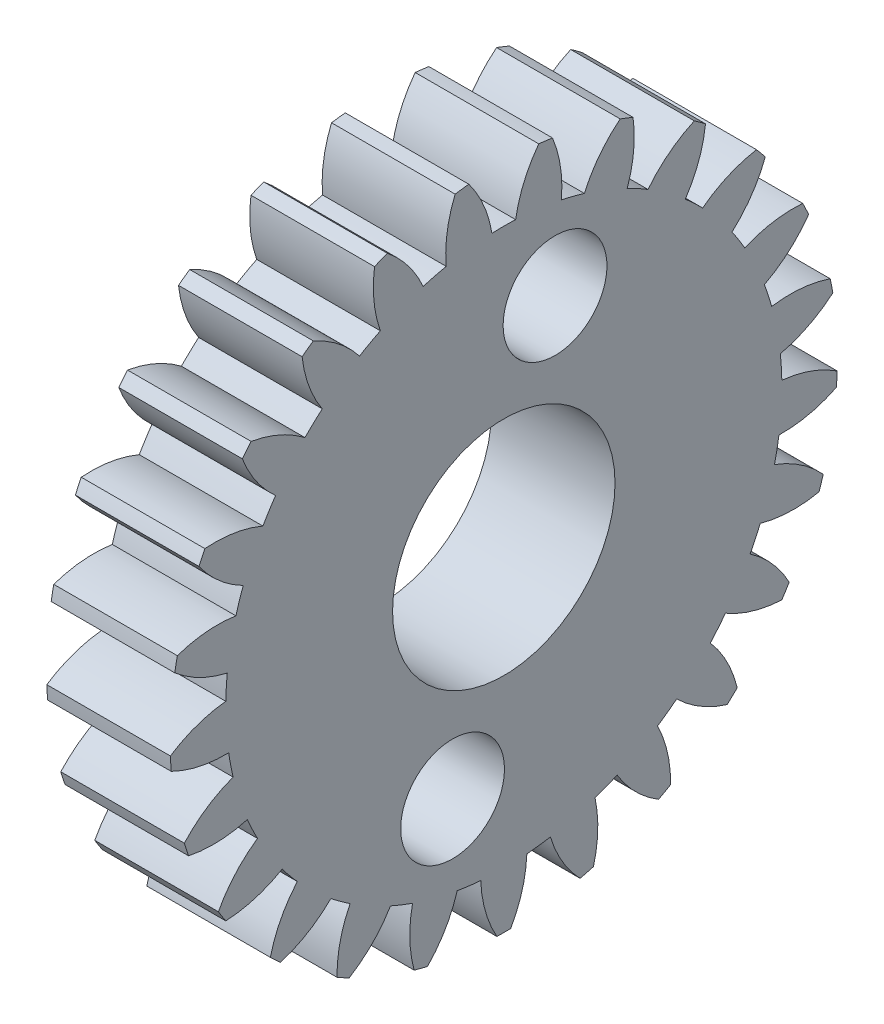
SolidWorks part; units mm, degrees
ref_plane "Plane1" through (0, 0, 0) normal (0, 0, 1) x (1, 0, 0)
ref_plane "Plane2" through (0, 0, 0) normal (0, 1, 0) x (1, 0, 0)
ref_plane "Plane3" through (0, 0, 0) normal (1, 0, 0) x (0, 0, -1)
sketch "HoldingSke" plane through (0, 0, 0) normal (0, 1, 0) x (1, 0, 0)
  line L0 (0, 0) -> (0.9063, -0.4226)
  line L1 (-15, 0) -> (100, 0) construction
  line L2 (0, 0) -> (-2.1039, 2.3779)
  line L3 (0, 0) -> (-11.863, 4.5341)
  line L4 (0, 0) -> (7.8269, 3.6497)
  line L5 (0, 0) -> (-46.8476, -17.4728)
  line L6 (0, 0) -> (-4.1448, -2.7965)
  line L7 (-2.1039, 2.3779) -> (8.6586, 51.2059)
  line L8 (-76.2, 54.61) -> (-74.8, 54.61)
  line L9 (-71.009, 38.7566) -> (-53.1078, 45.2721)
  line L10 (-76.2, 71.12) -> (104.1128, 71.12)
  line L11 (0, 0) -> (-5, 0)
  line L12 (-76.2, 101.6) -> (-76.162, 101.6)
  line L13 (24.9733, 27.94) -> (52.9518, 28.4284)
  line L14 (24.9733, 27.94) -> (24.9743, 27.94)
  line L15 (24.9733, 27.94) -> (100.4006, 29.5858)
  line L16 (-63.627, -1) -> (-12.827, -1)
  circle A0 centre (0, 0) radius 4.5
  circle A1 centre (0, 0) radius 11.249
  circle A2 centre (0, 0) radius 37.5
  circle A3 centre (0, 0) radius 4.5
  dimension "MHD" = 22.498
  dimension "Hub_dia" = 75
  dimension "Bore" = 9
  dimension "MBD" = 9
  dimension "Num_teeth" = 25
  dimension "Pitch" = 1
  dimension "Overall_len" = 50
  dimension "Show_teeth" = 25
  dimension "Thickness" = 5
  dimension "OAL" = 50.0001
  dimension "T_dim" = 1.4
  dimension "Ap" = 20
  dimension "H" = 19.05
  dimension "Pitch_radius" = 180.3128
  dimension "Width" = 5
  dimension "Backlash" = 0.038
  dimension "Addendum_fac" = 1
  dimension "Dedendum_fac" = 1.25
  dimension "Clearance_fac" = 0.25
  dimension "Dedendum_add" = 0.001
  dimension "Module" = 1
sketch "BasProSke" plane through (0, 0, 0) normal (0, 1, 0) x (1, 0, 0)
  line L0 (-10, 0) -> (60, 0) construction
  line L1 (0, 0) -> (0, 13.5)
  line L2 (0, 0) -> (5, 0)
  line L3 (5, 0) -> (5, 13.5)
  line L4 (5, 13.5) -> (0, 13.5)
  dimension "Thickness" = 5
  dimension "Diameter" = 27
revolve "Base-Revolve" add sketch "BasProSke" angle 360 about L0
sketch "TooCutSke" plane through (0, 0, 0) normal (1, 0, 0) x (0, 0, -1)
  line L1 (0, 0) -> (0, 107) construction
  line L2 (0, 0) -> (-0.8514, 12.471) construction
  line L3 (0, 0) -> (-3.1282, 24.7619) construction
  line L4 (-0.8514, 12.471) -> (-1.5641, 12.3809) construction
  arc A0 (0.4801, 11.2388) -> (-0.4801, 11.2388) centre (0, 0) ccw
  arc A1 (1.4322, 13.4494) -> (-1.4322, 13.4494) centre (0, 0) ccw
  circle A2 centre (0, 0) radius 12.5 construction
  circle A3 centre (0, 0) radius 11.7462 construction
  arc A4 (-0.4801, 11.2388) -> (-1.4322, 13.4494) centre (-5.4133, 10.4244) ccw
  arc A5 (1.4322, 13.4494) -> (0.4801, 11.2388) centre (5.4133, 10.4244) ccw
  dimension "Root_dia" = 22.498
  dimension "Overcut_dia" = 27.0508
  dimension "Pitch_dia" = 25
  dimension "Base_dia" = 23.4923
  dimension "Flank_rad" = 5
  dimension "Half_ang" = 7.2
  dimension "Half_CT" = 0.7184
extrude "ToothCut" cut sketch "TooCutSke" along normal through all
fillet "Breaks" [suppressed] radius 0.02
fillet "RootFillets" [suppressed] radius 0.251
pattern_circular "TeethCuts" count 25 every 14.4 about axis through (-10, 0, 0) along (1, 0, 0) of "ToothCut", "RootFillets", "Breaks"
sketch "HubNeaOneSke" plane through (0, 0, 0) normal (-1, 0, 0) x (0, 0, 1)
  circle A0 centre (0, 0) radius 11.249
  dimension "Diameter" = 22.498
extrude "HubNearOne" [suppressed] add sketch "HubNeaOneSke" along normal blind 45.0001
sketch "HubNeaBotSke" plane through (0, 0, 0) normal (-1, 0, 0) x (0, 0, 1)
  circle A0 centre (0, 0) radius 11.249
  dimension "Diameter" = 22.498
extrude "HubNearBoth" [suppressed] add sketch "HubNeaBotSke" along normal blind 22.5
ref_plane "FarPln" through (5, 0, 0) normal (1, 0, 0) x (0, 0, -1)
sketch "HubFarSke" plane through (5, 0, 0) normal (1, 0, 0) x (0, 0, -1)
  circle A0 centre (0, 0) radius 11.249
  dimension "Diameter" = 22.498
extrude "HubFar" [suppressed] add sketch "HubFarSke" along normal blind 22.5
sketch "BorSke" plane through (0, 0, 0) normal (1, 0, 0) x (0, 0, -1)
  circle A0 centre (0, 0) radius 4.5
  dimension "Diameter" = 9
extrude "Bore" cut sketch "BorSke" along normal mid plane 100.0001
sketch "KeySke" plane through (0, 0, 0) normal (1, 0, 0) x (0, 0, -1)
  line L0 (-1.5, 0) -> (-1.5, 5.9)
  line L1 (-1.5, 5.9) -> (1.5, 5.9)
  line L2 (1.5, 5.9) -> (1.5, 0)
  line L3 (0, 0) -> (0, 34) construction
  line L4 (-1.5, 0) -> (1.5, 0)
  dimension "Offset" = 5.9
  dimension "Width" = 3
extrude "Keyway" [suppressed] cut sketch "KeySke" along normal mid plane 100.0001
pattern_circular "Keyway2" [suppressed] count 2 every 90 about axis through (-10, 0, 0) along (1, 0, 0)
sketch "Esquisse3" plane through (0, 0, 0) normal (-1, 0, 0) x (0, 0, 1)
  circle A0 centre (-2.0726, 7.78) radius 2.1
  dimension "D1" = 7.78
extrude "Enlèv. mat.-Extru.1" cut sketch "Esquisse3" against normal through all
pattern_circular "Répétition circulaire1" count 2 over 360 about axis through (0, 0, 0) along (1, 0, 0) of "Enlèv. mat.-Extru.1"
equation "' \"Module@HoldingSke\" = 6.35"
equation "' \"Num_teeth@HoldingSke\" = 12"
equation "' \"Ap@HoldingSke\" =  20"
equation "' \"Ap@HoldingSke\" = 20"
equation "' \"Width@HoldingSke\" = 0.5 * 25.4"
equation "' \"Hub_dia@HoldingSke\"= 1 * 25.4"
equation "' \"Hub_dia@HoldingSke\" = 1 * 25.4"
equation "' \"Overall_len@HoldingSke\" = 1.0 * 25.4"
equation "' \"Bore@HoldingSke\" = 0.75 * 25.4"
equation "' \"T_dim@HoldingSke\" = 0.1 * 25.4"
equation "' \"Width@KeySke\" = 0.25 * 25.4"
equation "' \"Show_teeth@HoldingSke\" = 13"
equation "' \"Backlash@HoldingSke\" = 0.009 * 25.4"
equation "' \"Addendum_fac@HoldingSke\" = 1.0"
equation "' \"Dedendum_fac@HoldingSke\" = 1.25"
equation "' \"Dedendum_add@HoldingSke\" = 0.00005 * 25.4"
equation "' \"Clearance_fac@HoldingSke\" = 0.25"
equation "\"Pitch@HoldingSke\" = 1 / \"Module@HoldingSke\""
equation "\"Overcut_dia@TooCutSke\" = (\"Num_teeth@HoldingSke\" + 2 * \"Addendum_fac@HoldingSke\") / \"Pitch@HoldingSke\" + 0.002 * 25.4"
equation "\"Pitch_dia@TooCutSke\" = \"Num_teeth@HoldingSke\" / \"Pitch@HoldingSke\""
equation "\"Base_dia@TooCutSke\" = \"Num_teeth@HoldingSke\" / \"Pitch@HoldingSke\" * cos((\"Ap@HoldingSke\"  * 3.14159265 / 180))"
equation "\"Root_dia@TooCutSke\" = (\"Num_teeth@HoldingSke\" + 2) / \"Pitch@HoldingSke\" - 2 * (\"Addendum_fac@HoldingSke\" + \"Dedendum_fac@HoldingSke\") / \"Pitch@HoldingSke\" - \"Dedendum_add@HoldingSke\" * 2"
equation "\"Half_ang@TooCutSke\" = 180 / \"Num_teeth@HoldingSke\""
equation "\"Half_CT@TooCutSke\" = \"Num_teeth@HoldingSke\" / \"Pitch@HoldingSke\" * sin((3.14159265 / 2 / \"Num_teeth@HoldingSke\")) / 2 - 7 * \"Backlash@HoldingSke\" / 4"
equation "\"Flank_rad@TooCutSke\" = \"Num_teeth@HoldingSke\" / \"Pitch@HoldingSke\" / 5"
equation "\"Radius@RootFillets\" = \"Clearance_fac@HoldingSke\" / \"Pitch@HoldingSke\" + \"Dedendum_add@HoldingSke\""
equation "\"Break_rad@Breaks\" = 0.02 / \"Pitch@HoldingSke\""
equation "\"Thickness@HoldingSke\" = \"Width@HoldingSke\""
equation "\"OAL@HoldingSke\" = \"Thickness@HoldingSke\""
equation "\"MHD@HoldingSke\" = (\"Num_teeth@HoldingSke\" + 2) / \"Pitch@HoldingSke\" - 2 * (\"Addendum_fac@HoldingSke\" + \"Dedendum_fac@HoldingSke\")  / \"Pitch@HoldingSke\" - \"Dedendum_add@HoldingSke\" * 2"
equation "\"MBD@HoldingSke\" = (\"Num_teeth@HoldingSke\" + 2) / \"Pitch@HoldingSke\" - 2 * (\"Addendum_fac@HoldingSke\" + \"Dedendum_fac@HoldingSke\")  / \"Pitch@HoldingSke\" - \"Dedendum_add@HoldingSke\" * 2 - 0.002 * 25.4"
equation "\"MHD@HoldingSke\" = ((sgn( \"MHD@HoldingSke\" - \"Hub_dia@HoldingSke\" )-1)*( \"MHD@HoldingSke\" - \"Hub_dia@HoldingSke\" ))/-2+ \"Hub_dia@HoldingSke\""
equation "\"MBD@HoldingSke\" = ((sgn( \"MBD@HoldingSke\" - \"Bore@HoldingSke\" )-1)*( \"MBD@HoldingSke\" - \"Bore@HoldingSke\" ))/-2+ \"Bore@HoldingSke\""
equation "\"OAL@HoldingSke\" = ((sgn( \"OAL@HoldingSke\" - \"Overall_len@HoldingSke\" )+1)*( \"OAL@HoldingSke\" - \"Overall_len@HoldingSke\" ))/2 + \"Overall_len@HoldingSke\" + 0.000002 * 25.4"
equation "\"Num_teeth@TeethCuts\" = int( \"Show_teeth@HoldingSke\" ) + 1"
equation "\"Num_teeth@TeethCuts\" = ((sgn( \"Num_teeth@TeethCuts\" - \"Num_teeth@HoldingSke\" )-1)*( \"Num_teeth@TeethCuts\" - \"Num_teeth@HoldingSke\" ))/-2+ \"Num_teeth@HoldingSke\""
equation "\"Num_teeth@TeethCuts\" = ((sgn( \"Num_teeth@TeethCuts\" - 2.0)+1)*( \"Num_teeth@TeethCuts\" - 2.0))/2 +2.0"
equation "\"Angle@TeethCuts\" = 360.0 / \"Num_teeth@HoldingSke\""
equation "\"Diameter@BasProSke\" = (\"Num_teeth@HoldingSke\" + 2 * \"Addendum_fac@HoldingSke\") / \"Pitch@HoldingSke\""
equation "\"Thickness@BasProSke\"  = \"Thickness@HoldingSke\""
equation "' \"Fillet_rad@BasProSke\" =  \"Thickness@HoldingSke\" * 0.05"
equation "' \"Fillet_rad@BasProSke\" = \"Thickness@HoldingSke\" * 0.05"
equation "\"MHD@HoldingSke\" = ((sgn( \"MHD@HoldingSke\" - \"Root_dia@TooCutSke\" )-1)*( \"MHD@HoldingSke\" - \"Root_dia@TooCutSke\" ))/-2+ \"Root_dia@TooCutSke\""
equation "\"Diameter@HubNeaOneSke\" = \"MHD@HoldingSke\""
equation "\"Length@HubNearOne\" = \"OAL@HoldingSke\" - \"Thickness@BasProSke\""
equation "\"Diameter@HubNeaBotSke\" = \"MHD@HoldingSke\""
equation "\"Length@HubNearBoth\" = ( \"OAL@HoldingSke\" - \"Thickness@BasProSke\" ) / 2.0"
equation "\"Thickness@FarPln\" = \"Thickness@BasProSke\""
equation "\"Diameter@HubFarSke\" = \"MHD@HoldingSke\""
equation "\"Length@HubFar\" = ( \"OAL@HoldingSke\" - \"Thickness@BasProSke\" ) / 2.0"
equation "\"Diameter@BorSke\" = \"MBD@HoldingSke\""
equation "\"D1@Bore\" = \"OAL@HoldingSke\" * 2.0"
equation "\"D1@Keyway\" = \"OAL@HoldingSke\" * 2.0"
equation "\"Offset@KeySke\" = \"T_dim@HoldingSke\" + \"MBD@HoldingSke\" / 2.0"
